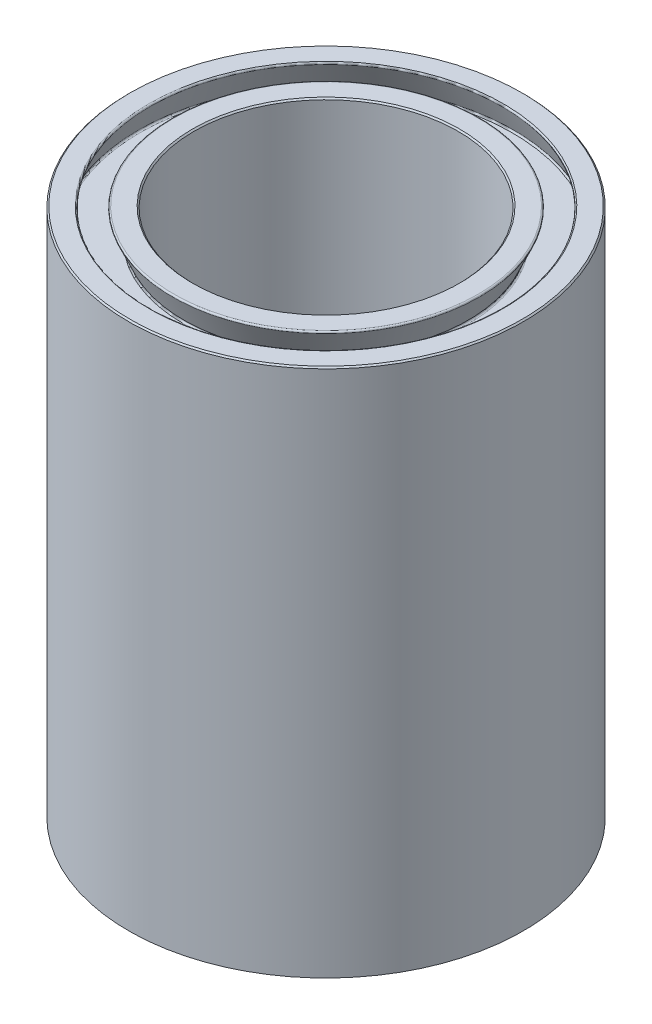
SolidWorks part; units mm, degrees
ref_plane "Front Plane" through (0, 0, 0) normal (0, 0, 1) x (1, 0, 0)
ref_plane "Top Plane" through (0, 0, 0) normal (0, 1, 0) x (1, 0, 0)
ref_plane "Right Plane" through (0, 0, 0) normal (1, 0, 0) x (0, 0, -1)
sketch "Sketch1" plane through (0, 0, 0) normal (0, 0, 1) x (1, 0, 0)
  line L0 (0, 0) -> (-56.896, 0)
  line L1 (-56.896, 0) -> (-56.896, 152.4)
  line L3 (-38.1, 152.4) -> (-38.1, 34.925)
  line L4 (-12.7, 9.525) -> (0, 9.525)
  line L5 (0, 9.525) -> (0, 0)
  line L12 (-56.896, 152.4) -> (-50.4825, 152.4)
  line L13 (-50.4825, 152.4) -> (-54.2992, 143.8275)
  line L14 (-54.2992, 143.8275) -> (-40.6968, 143.8275)
  line L15 (-40.6968, 143.8275) -> (-44.5135, 152.4)
  line L16 (-44.5135, 152.4) -> (-38.1, 152.4)
  arc A0 (-38.1, 34.925) -> (-12.7, 9.525) centre (-12.7, 34.925) ccw
  point P9 (-38.1, 9.525)
  point P14 (0, 0)
  point P15 (0, 0)
  dimension "D3" = 25.4
  dimension "D1" = 38.1
  dimension "D2" = 152.4
  dimension "D4" = 18.796
  dimension "D5" = 9.525
  dimension "D6" = 66
  dimension "D7" = 66
  dimension "D8" = 5.969
  dimension "D9" = 8.5725
revolve "Revolve1" add sketch "Sketch1" angle 360 about L5
sketch "Sketch2" [suppressed] plane through (0, 0, 0) normal (0, -1, 0) x (1, 0, 0)
  circle A0 centre (0, 0) radius 12.7 construction
  circle A1 centre (0, 12.7) radius 2.032
  point P3 (0, 12.7)
  point P7 (8.9803, 8.9803)
  point P8 (12.7, 0)
  point P9 (8.9803, -8.9803)
  point P10 (0, -12.7)
  point P11 (-8.9803, -8.9803)
  point P12 (-12.7, 0)
  point P13 (-8.9803, 8.9803)
  point P14 (0, 0)
  dimension "D1" = 25.4
  dimension "D3" = 4.064
  dimension "D2" = 8
extrude "Cut-Extrude1" [suppressed] cut sketch "Sketch2" against normal up to next draft 4.35 contours A1
pattern_circular "CirPattern1" [suppressed] count 4 over 360
fillet "Fillet1" radius 0.3969 4 edges at (-40.6968, 143.8275, 0) (-50.4825, 152.4, 0) (-54.2992, 143.8275, 0) (-44.5135, 152.4, 0)
chamfer "Chamfer1" distance 0.3969 angle 45 2 edges at (-38.1, 152.4, 0) (-56.896, 152.4, 0)
